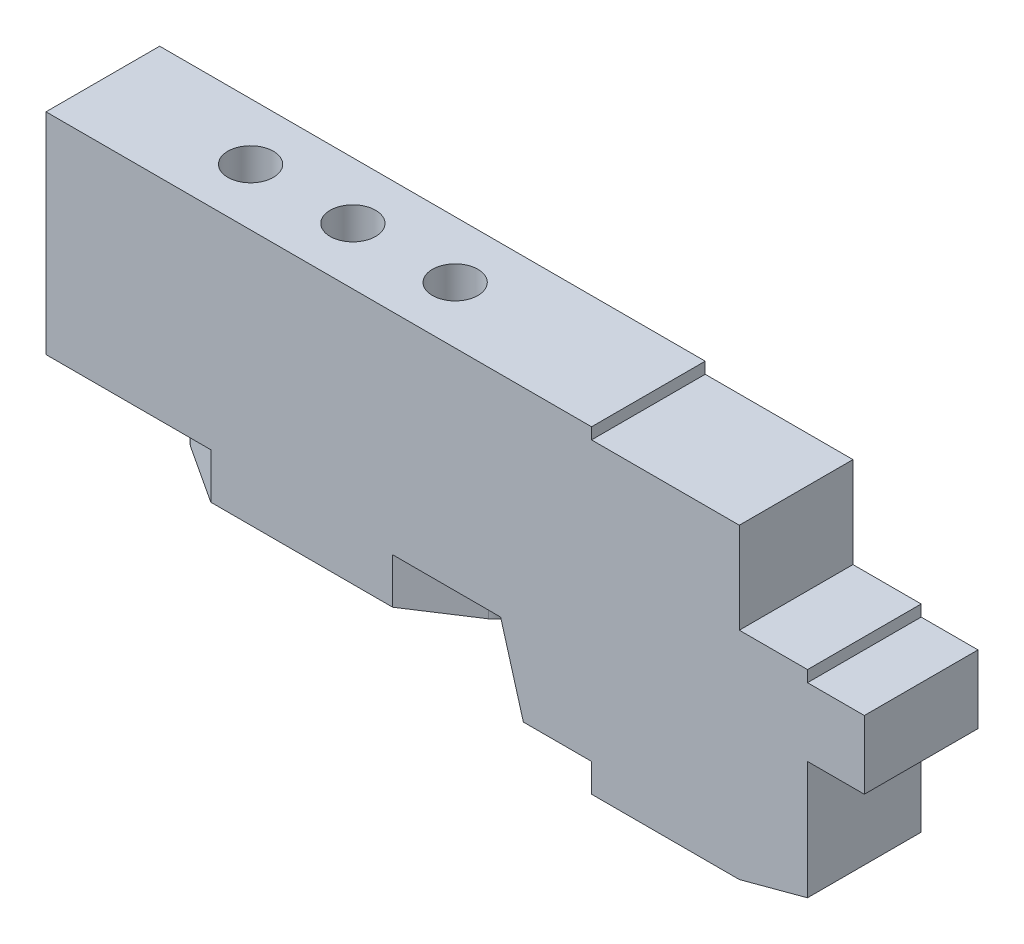
SolidWorks part; units mm, degrees
ref_plane "前视基准面" through (0, 0, 0) normal (0, 0, 1) x (1, 0, 0)
ref_plane "上视基准面" through (0, 0, 0) normal (0, 1, 0) x (1, 0, 0)
ref_plane "右视基准面" through (0, 0, 0) normal (1, 0, 0) x (0, 0, -1)
sketch "草图1" plane through (0, 0, 0) normal (0, 0, 1) x (1, 0, 0)
  line L0 (18, -16.25) -> (16, -9.25)
  line L1 (16, -9.25) -> (-24, -9.25)
  line L2 (24, 8.25) -> (24, 9.25)
  line L3 (24, 9.25) -> (-24, 9.25)
  line L4 (-24, -9.25) -> (-24, 9.25)
  line L5 (24, -9.25) -> (-24, 9.25) construction
  line L6 (24, 9.25) -> (-24, -9.25) construction
  line L7 (18, -16.25) -> (24, -16.25)
  line L8 (24, -16.25) -> (24, -18.75)
  line L9 (24, -18.75) -> (37, -18.75)
  line L10 (37, -18.75) -> (43, -17.1423)
  line L11 (43, -17.1423) -> (43, -6.75)
  line L12 (43, -6.75) -> (48, -6.75)
  line L13 (48, -6.75) -> (48, -0.75)
  line L14 (48, -0.75) -> (43, -0.75)
  line L15 (43, -0.75) -> (43, 0.25)
  line L16 (43, 0.25) -> (37, 0.25)
  line L17 (37, 0.25) -> (37, 8.25)
  line L18 (37, 8.25) -> (24, 8.25)
  point P0 (0, 0)
  dimension "D1" = 18.5
  dimension "D2" = 48
  dimension "D3" = 8
  dimension "D4" = 7
  dimension "D5" = 13
  dimension "D6" = 67
  dimension "D7" = 5
  dimension "D8" = 1
  dimension "D9" = 8
  dimension "D10" = 12
  dimension "D11" = 1
  dimension "D12" = 6
  dimension "D13" = 15
  dimension "D14" = 6
extrude "凸台-拉伸1" add sketch "草图1" along normal blind 10
sketch "草图2" plane through (0, -9.25, 0) normal (0, -1, 0) x (1, 0, 0)
  line L0 (-24, 5) -> (12.1485, 5) construction
  line L1 (-24, 10) -> (-24, 0) construction
  line L2 (-14.5934, 6.6747) -> (-9.5, 10)
  line L3 (-24, 10) -> (16, 10) construction
  line L4 (-9.5, 10) -> (6.5, 10)
  line L5 (-14.5934, 3.3253) -> (-9.5, 0)
  line L6 (-24, 0) -> (16, 0) construction
  line L7 (-9.5, 0) -> (6.5, 0)
  line L8 (6.5, 10) -> (11.5934, 6.6747)
  line L9 (6.5, 0) -> (11.5934, 3.3253)
  line L10 (-1.5, 10) -> (-1.5, 2.5867) construction
  arc A0 (-14.5934, 6.6747) -> (-14.5934, 3.3253) centre (-13.5, 5) ccw
  arc A1 (11.5934, 3.3253) -> (11.5934, 6.6747) centre (10.5, 5) ccw
  circle A2 centre (-6.75, 5) radius 2
  circle A3 centre (3.75, 5) radius 2
  dimension "D1" = 4
  dimension "D2" = 10.5
  dimension "D6" = 4
  dimension "D3" = 24
  dimension "D4" = 16
  dimension "D5" = 10.5
extrude "凸台-拉伸2" add sketch "草图2" along normal blind 4
cosmetic thread "装饰螺纹线1" parameters "D2"=5
cosmetic thread "装饰螺纹线2" parameters "D2"=5
sketch "草图3" plane through (0, 9.25, 0) normal (0, 1, 0) x (1, 0, 0)
  line L0 (-24, -5) -> (-2.7768, -5) construction
  line L1 (-24, -10) -> (-24, 0) construction
  circle A0 centre (-2, -5) radius 2
  circle A1 centre (-11, -5) radius 2
  circle A2 centre (7, -5) radius 2
  dimension "D1" = 4
  dimension "D2" = 9
  dimension "D3" = 9
  dimension "D4" = 22
extrude "切除-拉伸1" cut sketch "草图3" against normal blind 10
cosmetic thread "装饰螺纹线3" parameters "D2"=5
cosmetic thread "装饰螺纹线4" parameters "D2"=5
cosmetic thread "装饰螺纹线5" parameters "D2"=5
